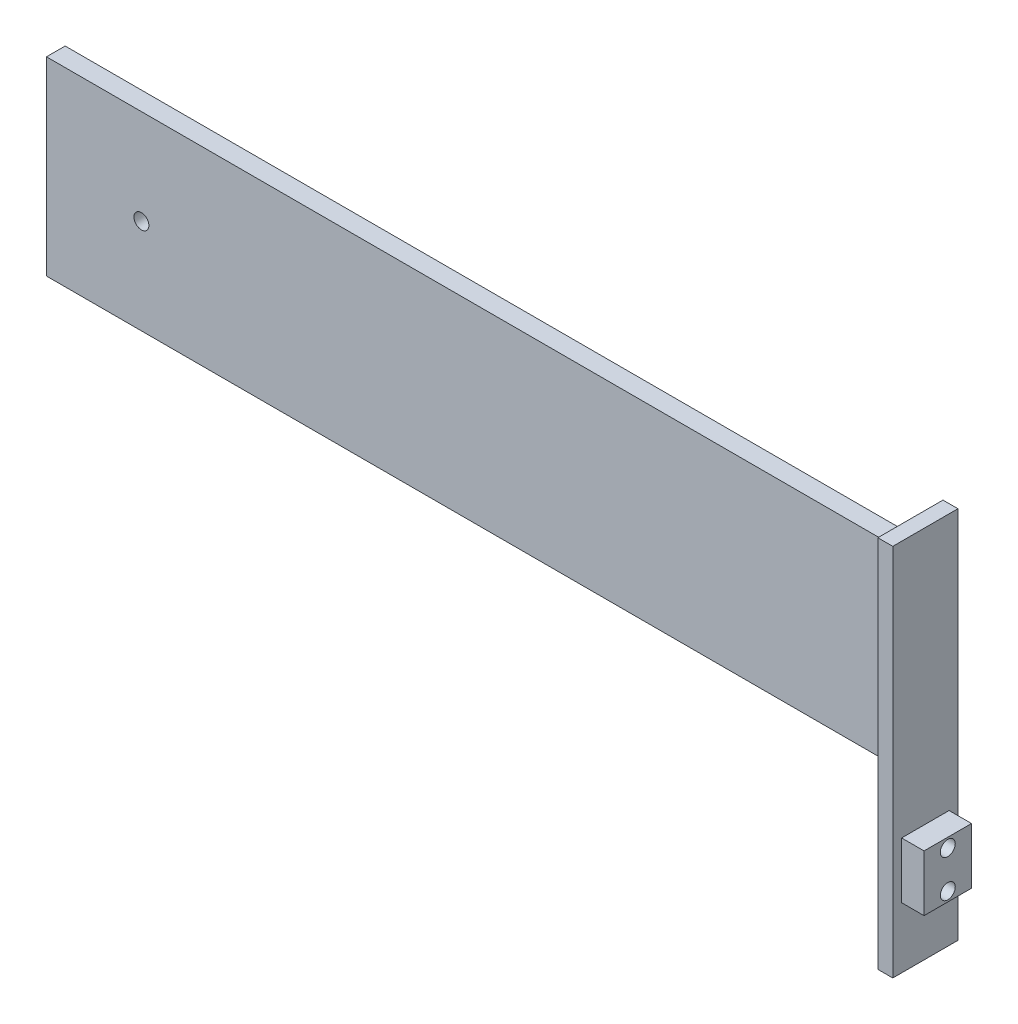
SolidWorks part; units mm, degrees
ref_plane "Front Plane" through (0, 0, 0) normal (0, 0, 1) x (1, 0, 0)
ref_plane "Top Plane" through (0, 0, 0) normal (0, 1, 0) x (1, 0, 0)
ref_plane "Right Plane" through (0, 0, 0) normal (1, 0, 0) x (0, 0, -1)
sketch "Sketch1" plane through (0, 0, 0) normal (0, 0, 1) x (1, 0, 0)
  line L1 (-114.3, 25.4) -> (114.3, 25.4)
  line L2 (-114.3, 25.4) -> (-114.3, -25.4)
  line L3 (-114.3, -25.4) -> (114.3, -25.4)
  line L4 (114.3, 25.4) -> (114.3, -25.4)
  line L5 (-114.3, 25.4) -> (114.3, -25.4) construction
  line L6 (-114.3, -25.4) -> (114.3, 25.4) construction
  point P0 (0, 0)
  dimension "D1" = 228.6
  dimension "D2" = 50.8
extrude "Boss-Extrude1" add sketch "Sketch1" along normal blind 5
sketch "Sketch2" plane through (0, 0, 5) normal (0, 0, 1) x (1, 0, 0)
  line L7 (-88.9, 25.4) -> (-88.9, -25.4) construction
  line L8 (-114.3, 0) -> (-63.5, 0) construction
  circle A0 centre (-88.9, 0) radius 2
  dimension "D2" = 4
extrude "Cut-Extrude1" cut sketch "Sketch2" against normal through all
sketch "Sketch3" plane through (114.3, 0, 0) normal (1, 0, 0) x (0, 0, -1)
  line L0 (-2.5, 25.4) -> (-2.5, -25.4) construction
  line L1 (-5, 25.4) -> (0, 25.4) construction
  line L2 (-5, -25.4) -> (0, -25.4) construction
  line L3 (0, 0) -> (-5, 0) construction
  line L4 (-5, -25.4) -> (-5, 25.4) construction
  line L5 (0, -25.4) -> (0, 25.4) construction
  line L6 (-11.2156, 31.4) -> (6.2156, 31.4)
  line L7 (-11.2156, 31.4) -> (-11.2156, -68.6)
  line L8 (-11.2156, -68.6) -> (6.2156, -68.6)
  line L9 (6.2156, 31.4) -> (6.2156, -68.6)
  line L10 (-11.2156, 31.4) -> (6.2156, -68.6) construction
  line L11 (-11.2156, -68.6) -> (6.2156, 31.4) construction
  point P11 (-2.5, -18.6)
  point P16 (-2.5, 31.4)
  dimension "D1" = 100
  dimension "D2" = 6
  dimension "D3" = 6.2156
extrude "Boss-Extrude2" add sketch "Sketch3" along normal blind 4
sketch "Sketch4" plane through (118.3, 0, 0) normal (1, 0, 0) x (0, 0, -1)
  line L0 (-2.5, 31.4) -> (-2.5, -68.6) construction
  line L1 (6.2156, 31.4) -> (-11.2156, 31.4) construction
  line L2 (-11.2156, -68.6) -> (6.2156, -68.6) construction
  line L3 (-11.2156, -18.6) -> (6.2156, -18.6) construction
  line L4 (-11.2156, 31.4) -> (-11.2156, -68.6) construction
  line L5 (6.2156, -68.6) -> (6.2156, 31.4) construction
  line L7 (-8.85, -37.34) -> (3.85, -37.34)
  line L8 (-8.85, -37.34) -> (-8.85, -52.34)
  line L9 (-8.85, -52.34) -> (3.85, -52.34)
  line L10 (3.85, -37.34) -> (3.85, -52.34)
  line L11 (-8.85, -37.34) -> (3.85, -52.34) construction
  line L12 (-8.85, -52.34) -> (3.85, -37.34) construction
  point P12 (-2.5, -44.84)
  dimension "D1" = 16.26
  dimension "D2" = 15
  dimension "D3" = 12.7
extrude "Boss-Extrude3" add sketch "Sketch4" along normal blind 6
sketch "Sketch5" plane through (124.3, 0, 0) normal (1, 0, 0) x (0, 0, -1)
  line L0 (-2.5, -37.34) -> (-2.5, -52.34) construction
  line L1 (3.85, -37.34) -> (-8.85, -37.34) construction
  line L2 (-8.85, -52.34) -> (3.85, -52.34) construction
  line L3 (-8.85, -44.84) -> (3.85, -44.84) construction
  line L4 (-8.85, -37.34) -> (-8.85, -52.34) construction
  line L5 (3.85, -52.34) -> (3.85, -37.34) construction
  circle A0 centre (-2.5, -39.84) radius 2
  circle A1 centre (-2.5, -49.84) radius 2
  dimension "D1" = 4
  dimension "D2" = 4
  dimension "D3" = 10
  dimension "D4" = 2.5
extrude "Cut-Extrude2" cut sketch "Sketch5" against normal up to next
sketch "Sketch6" plane through (114.3, 0, 0) normal (-1, 0, 0) x (0, 0, 1)
  circle A0 centre (2.5, -39.84) radius 3.5
  circle A1 centre (2.5, -49.84) radius 3.5
  dimension "D1" = 7
  dimension "D2" = 7
extrude "Cut-Extrude3" cut sketch "Sketch6" against normal blind 3
fillet "Fillet2" radius 2.54 4 edges at (114.3, 25.4, 2.5) (114.3, 0, 0) (114.3, -25.4, 2.5) (114.3, 0, 5)
